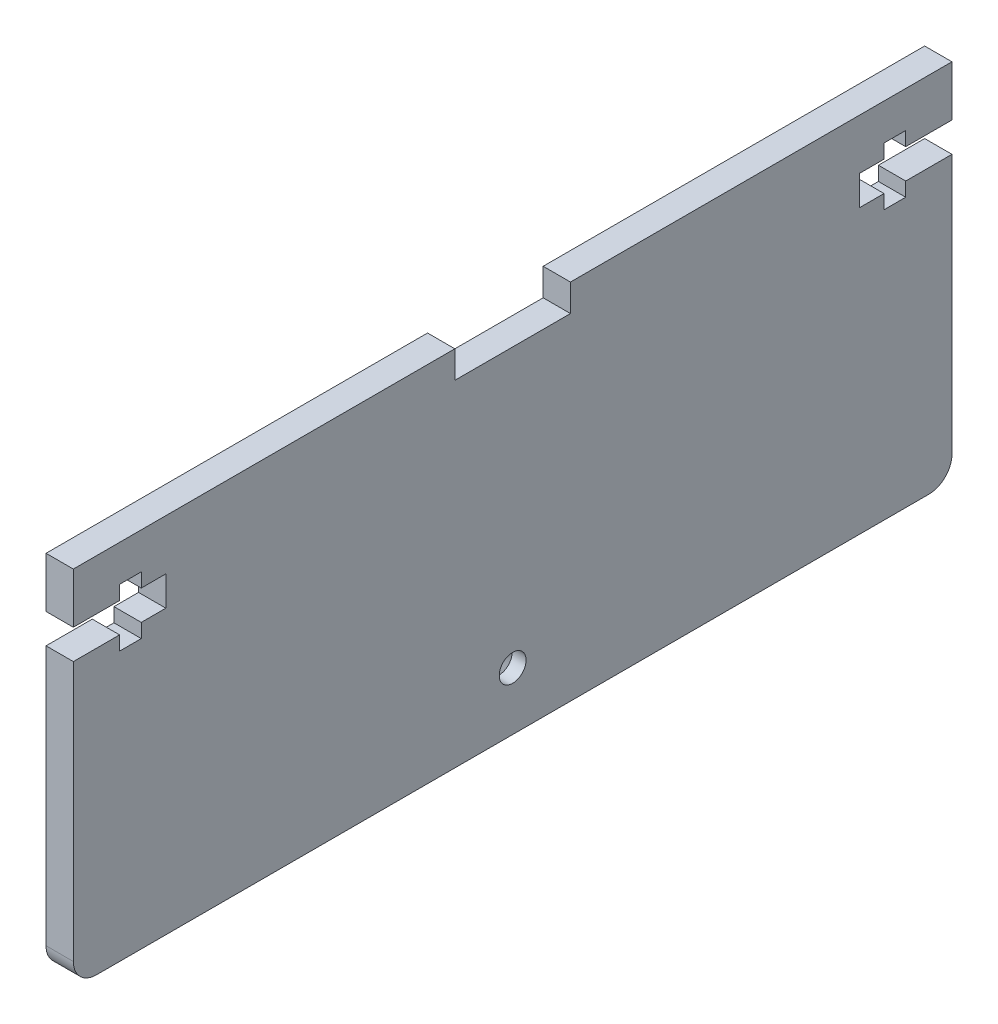
SolidWorks part; units mm, degrees
material "Acrylic (Medium-high impact)"
ref_plane "Front Plane" through (0, 0, 0) normal (0, 0, 1) x (1, 0, 0)
ref_plane "Top Plane" through (0, 0, 0) normal (0, 1, 0) x (1, 0, 0)
ref_plane "Right Plane" through (0, 0, 0) normal (1, 0, 0) x (0, 0, -1)
sketch "Sketch1" plane through (0, 0, 0) normal (1, 0, 0) x (0, 0, -1)
  line L1 (0, 0) -> (96.52, 0)
  line L2 (0, 0) -> (0, 39.878)
  line L3 (0, 39.878) -> (96.52, 39.878)
  line L4 (96.52, 0) -> (96.52, 39.878)
  dimension "D1" = 96.52
  dimension "D2" = 39.878
extrude "Boss-Extrude1" add sketch "Sketch1" along normal blind 3
hole_wizard "#32 (0.116) Diameter Hole1" positions "Sketch3" profile "Sketch2" hole size "#32" standard "ANSI Inch"
sketch "Sketch3" plane through (3, 0, 0) normal (1, 0, 0) x (0, 0, -1)
  line L0 (96.52, 39.878) -> (0, 39.878) construction
  line L1 (96.52, 0) -> (96.52, 39.878) construction
  point P0 (48.26, 6.35)
  dimension "D1" = 33.528
  dimension "D2" = 48.26
sketch "Sketch2" plane through (3, 6.35, -48.26) normal (0, 1, 0) x (0, 0, -1)
  line L0 (0, 0) -> (0, 2.4092)
  line L1 (0, 2.4092) -> (1.4732, 1.524)
  line L2 (1.4732, 1.524) -> (1.4732, 0)
  line L5 (1.4732, 0) -> (0, 0)
  line L10 (0, 2.4092) -> (-1.4732, 1.524) construction
  line L11 (0, -6.35) -> (0, 107.95) construction
  dimension "Hole Dia." = 2.9464
  dimension "Hole Depth" = 1.524
  dimension "Drill Angle" = 118
sketch "Sketch4" plane through (3, 0, 0) normal (1, 0, 0) x (0, 0, -1)
  line L0 (0, 34.338) -> (5.08, 34.338)
  line L1 (0, 39.878) -> (0, 0) construction
  line L2 (5.08, 34.338) -> (5.08, 35.8811)
  line L3 (5.08, 35.8811) -> (7.4613, 35.8811)
  line L4 (7.4613, 35.8811) -> (7.4613, 34.338)
  line L5 (7.4613, 34.338) -> (10.16, 34.338)
  line L6 (10.16, 34.338) -> (10.16, 31.0741)
  line L7 (10.16, 31.0741) -> (7.4613, 31.0741)
  line L8 (7.4613, 31.0741) -> (7.4613, 29.5311)
  line L9 (7.4613, 29.5311) -> (5.08, 29.5311)
  line L10 (5.08, 29.5311) -> (5.08, 31.0741)
  line L11 (5.08, 31.0741) -> (0, 31.0741)
  line L12 (0, 31.0741) -> (0, 34.338)
  line L13 (48.26, 39.878) -> (48.26, 0) construction
  line L14 (96.52, 39.878) -> (0, 39.878) construction
  line L15 (0, 0) -> (96.52, 0) construction
  line L16 (96.52, 31.0741) -> (96.52, 34.338)
  line L17 (91.44, 31.0741) -> (96.52, 31.0741)
  line L18 (91.44, 29.5311) -> (91.44, 31.0741)
  line L19 (89.0587, 29.5311) -> (91.44, 29.5311)
  line L20 (89.0587, 31.0741) -> (89.0587, 29.5311)
  line L21 (86.36, 31.0741) -> (89.0587, 31.0741)
  line L22 (86.36, 34.338) -> (86.36, 31.0741)
  line L23 (89.0587, 34.338) -> (86.36, 34.338)
  line L24 (89.0587, 35.8811) -> (89.0587, 34.338)
  line L25 (91.44, 35.8811) -> (89.0587, 35.8811)
  line L26 (91.44, 34.338) -> (91.44, 35.8811)
  line L27 (96.52, 34.338) -> (91.44, 34.338)
  dimension "D1" = 2.3813
  dimension "D2" = 3.2639
  dimension "D3" = 10.16
  dimension "D4" = 5.08
  dimension "D5" = 6.35
  dimension "D6" = 5.54
extrude "Cut-Extrude1" cut sketch "Sketch4" against normal blind 3
fillet "Fillet1" radius 2.54 2 edges at (1.5, 0, -96.52) (1.5, 0, 0)
sketch "Sketch5" plane through (3, 0, 0) normal (1, 0, 0) x (0, 0, -1)
  line L1 (96.52, 39.878) -> (0, 39.878) construction
  line L2 (41.91, 39.878) -> (54.61, 39.878)
  line L3 (41.91, 39.878) -> (41.91, 36.878)
  line L4 (41.91, 36.878) -> (54.61, 36.878)
  line L6 (54.61, 39.878) -> (54.61, 36.878)
  line L8 (96.52, 34.338) -> (96.52, 39.878) construction
  dimension "D1" = 12.7
  dimension "D2" = 3
  dimension "D3" = 41.91
extrude "Cut-Extrude2" cut sketch "Sketch5" against normal blind 3
